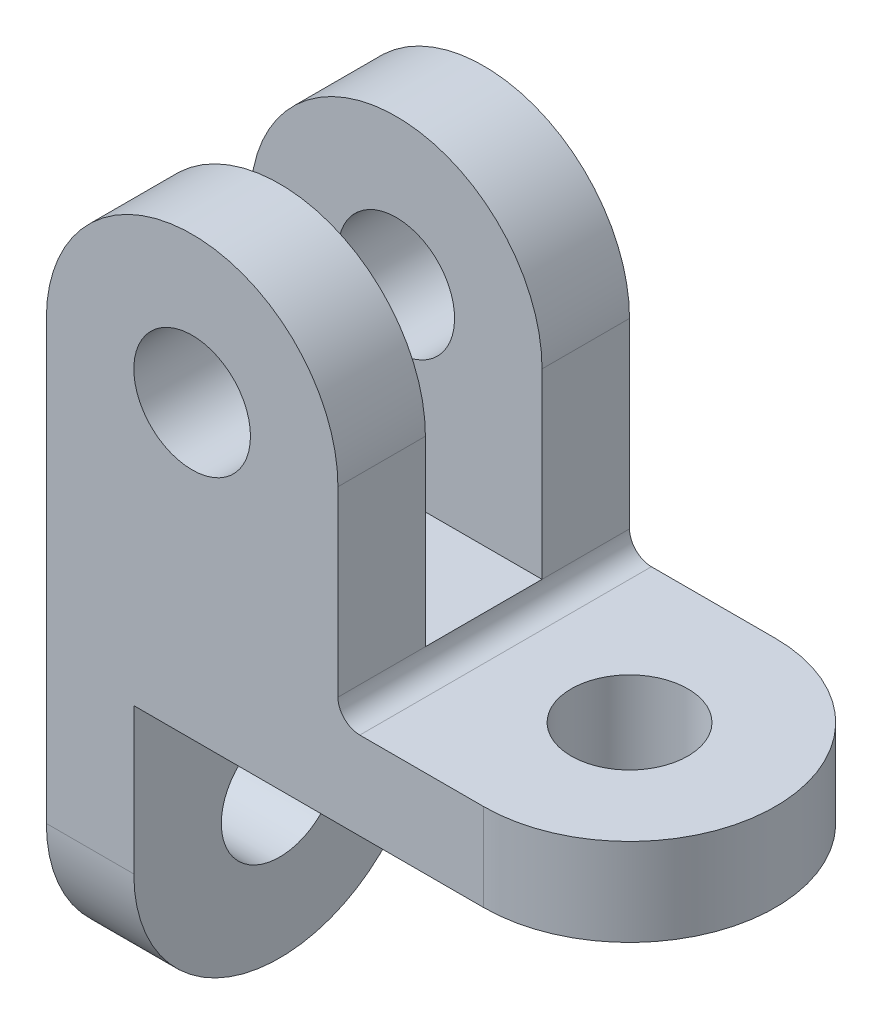
SolidWorks part; units mm, degrees
ref_plane "Front Plane" through (0, 0, 0) normal (0, 0, 1) x (1, 0, 0)
ref_plane "Top Plane" through (0, 0, 0) normal (0, 1, 0) x (1, 0, 0)
ref_plane "Right Plane" through (0, 0, 0) normal (1, 0, 0) x (0, 0, -1)
sketch "Sketch1" plane through (0, 0, 0) normal (0, 0, 1) x (1, 0, 0)
  line L0 (-52.0161, 0) -> (62.9366, 0) construction
  line L1 (0, 46.0369) -> (0, -50.3151) construction
  line L2 (23, 0) -> (60, 0)
  line L3 (60, 0) -> (60, -12)
  line L4 (60, -12) -> (-8, -12)
  line L5 (-8, -12) -> (-8, -52)
  line L6 (-8, -52) -> (-20, -52)
  line L7 (-20, -52) -> (-20, 28)
  line L9 (20, 28) -> (20, 3)
  line L10 (-20, -32) -> (-8, -32) construction
  arc A0 (20, 28) -> (-20, 28) centre (0, 28) ccw
  arc A1 (23, 0) -> (20, 3) centre (23, 3) cw
  point P18 (20, 0)
  dimension "D1" = 40
  dimension "D7" = 28
  dimension "D9" = 3
  dimension "D2" = 12
  dimension "D3" = 12
  dimension "D4" = 40
  dimension "D5" = 60
  dimension "D6" = 80
  dimension "D8" = 20
extrude "Boss-Extrude3" add sketch "Sketch1" along normal blind 40
sketch "Sketch10" plane through (0, 0, 0) normal (0, 1, 0) x (1, 0, 0)
  line L0 (60, -20) -> (-29.8062, -20) construction
  line L1 (60, -40) -> (60, 0) construction
  line L2 (20, -40) -> (-20.0745, -40)
  line L3 (-20.0745, -40) -> (-20, -28)
  line L4 (-20, -40) -> (-20, 0) construction
  line L5 (-20, -28) -> (20, -28)
  line L6 (20, -40) -> (20, 0) construction
  line L7 (-20, 0) -> (-20, -12)
  line L8 (-20, -12) -> (20, -12)
  line L9 (20, -40) -> (20, 0) construction
  line L10 (20, -28) -> (20, -40)
  line L11 (20, 0) -> (-20, 0)
  line L12 (20, 0) -> (23, 0)
  line L13 (-20, -12) -> (-20, -28)
  line L14 (20, -12) -> (20, -28)
  line L15 (60, 0) -> (23, 0) construction
  line L16 (60, -40) -> (23, -40) construction
  line L17 (60, 0) -> (40, 0)
  line L18 (60, -40) -> (60, 0)
  line L19 (60, -40) -> (40, -40)
  arc A0 (40, -40) -> (40, 0) centre (40, -20) ccw
  circle A1 centre (40, -20) radius 8
  dimension "D1" = 16
  dimension "D3" = 40
  dimension "D4" = 12
  dimension "D5" = 12
extrude "Cut-Extrude4" cut sketch "Sketch10" against normal blind 12 contours A0 L19 L18 | A0 L18 L17
sketch "Sketch11" plane through (0, 0, 0) normal (1, 0, 0) x (0, 0, -1)
  line L0 (-20, 48) -> (-20, -54.6883) construction
  line L1 (0, 48) -> (-40, 48) construction
  line L2 (-20, 48) -> (-28, 48)
  line L3 (-28, 48) -> (-28, 3)
  line L4 (-40, 3) -> (0, 3) construction
  line L5 (-28, 3) -> (-12, 3)
  line L6 (-12, 3) -> (-12, 48)
  line L7 (-12, 48) -> (-20, 48)
  dimension "D1" = 16
extrude "Cut-Extrude5" cut sketch "Sketch11" against normal mid plane 45
sketch "Sketch12" plane through (-8, 0, 0) normal (1, 0, 0) x (0, 0, -1)
  line L0 (-20, -52) -> (-20, 48.4414) construction
  line L1 (-40, -52) -> (0, -52) construction
  line L2 (-28, 48) -> (-40, 48) construction
  line L3 (0, -52) -> (0, -12) construction
  line L4 (-40, -52) -> (-40, -12) construction
  line L5 (0, -52) -> (0, -32)
  line L6 (-40, -52) -> (0, -52)
  line L7 (-40, -52) -> (-40, -32)
  circle A0 centre (-20, -32) radius 8
  arc A1 (-40, -32) -> (0, -32) centre (-20, -32) ccw
  line M1 (0, -52) -> (0, -12)
  line M3 (-40, -12) -> (-40, -52)
  line M4 (-40, -52) -> (0, -52)
  dimension "D1" = 40
  dimension "D2" = 16
  dimension "D3" = 80
extrude "Cut-Extrude7" cut sketch "Sketch12" against normal blind 45 contours A0 L0 | L0 A0 | A1 M3 M4 | A1 L6 M1
sketch "Sketch13" plane through (0, 0, 0) normal (0, 1, 0) x (1, 0, 0)
  line L0 (40, -20) -> (60, -20)
  arc A0 (40, -40) -> (40, 0) centre (40, -20) ccw construction
  circle A1 centre (40, -20) radius 8
  dimension "D1" = 16
extrude "Cut-Extrude8" cut sketch "Sketch13" against normal blind 45
sketch "Sketch14" plane through (0, 0, 0) normal (0, 0, 1) x (1, 0, 0)
  line L0 (0, 28) -> (20, 28)
  circle A0 centre (0, 28) radius 8
  dimension "D1" = 16
extrude "Cut-Extrude9" cut sketch "Sketch14" against normal blind 41 and the other way blind 54
sketch "Sketch15" plane through (0, 3, 0) normal (0, 1, 0) x (1, 0, 0)
  line L0 (-20, -12) -> (20, -12)
  line L1 (20, -12) -> (20, -28)
  line L2 (20, -28) -> (-20, -28)
  line L3 (-20, -28) -> (-20, -12)
